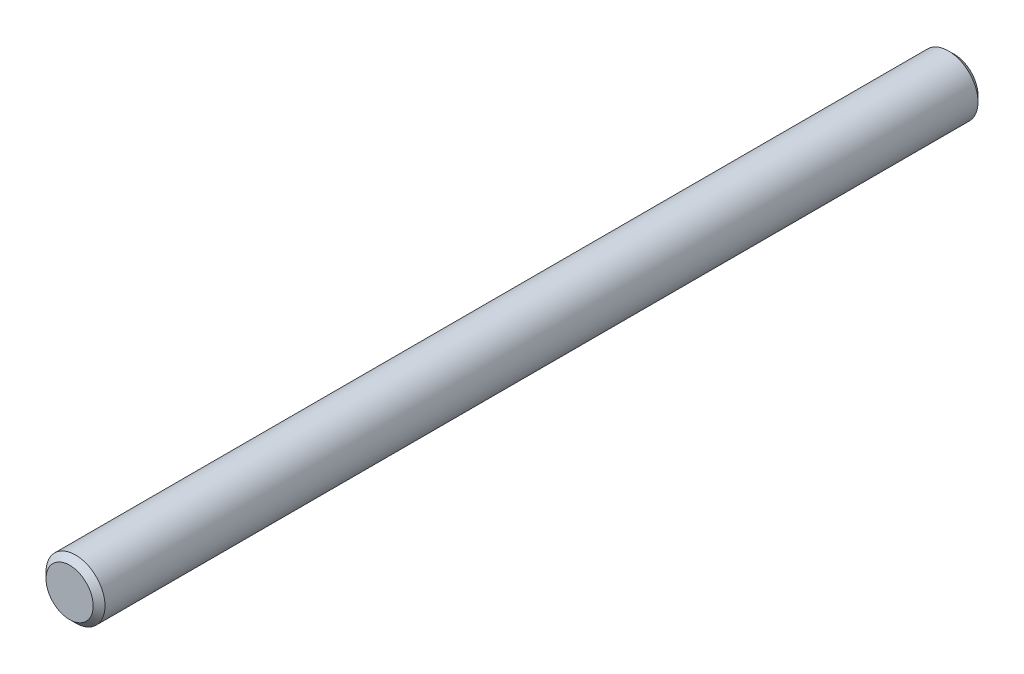
SolidWorks part; units mm, degrees
ref_plane "Plano frontal" through (0, 0, 0) normal (0, 0, 1) x (1, 0, 0)
ref_plane "Plano superior" through (0, 0, 0) normal (0, 1, 0) x (1, 0, 0)
ref_plane "Plano direito" through (0, 0, 0) normal (1, 0, 0) x (0, 0, -1)
sketch "Esboço1" plane through (0, 0, 0) normal (0, 0, 1) x (1, 0, 0)
  circle A0 centre (0, 0) radius 2.5
  dimension "D1" = 5
extrude "Ressalto-extrusão1" add sketch "Esboço1" along normal blind 75
ref_plane "Plano1" through (0, 0, 47) normal (0, 0, 1) x (1, 0, 0)
chamfer "Chanfro1" distance 0.5 angle 45 2 edges at (2.5, 0, 0) (2.5, 0, 75)
